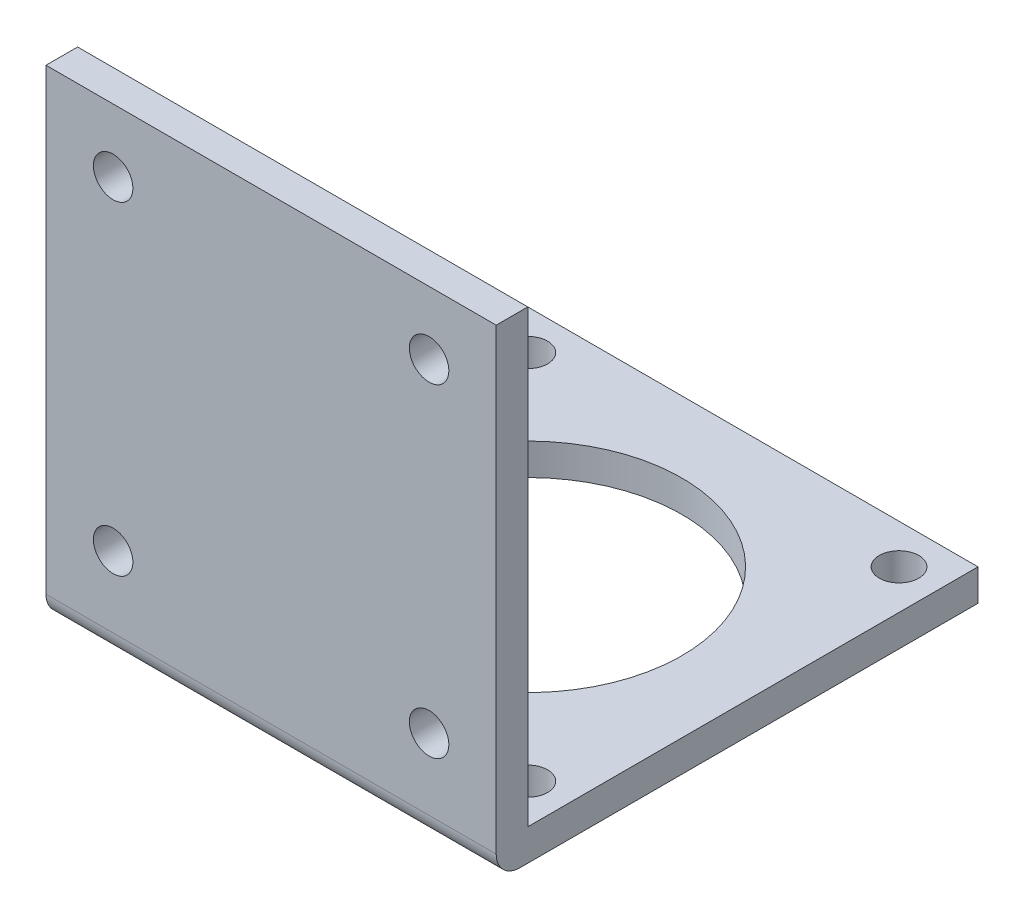
SolidWorks part; units mm, degrees
ref_plane "Front Plane" through (0, 0, 0) normal (0, 0, 1) x (1, 0, 0)
ref_plane "Top Plane" through (0, 0, 0) normal (0, 1, 0) x (1, 0, 0)
ref_plane "Right Plane" through (0, 0, 0) normal (1, 0, 0) x (0, 0, -1)
sketch "Sketch1" plane through (0, 0, 0) normal (1, 0, 0) x (0, 0, -1)
  line L0 (0, 0) -> (0, -61)
  line L1 (0, -61) -> (61, -61)
  line L2 (61, -61) -> (61, -57)
  line L3 (61, -57) -> (4, -57)
  line L4 (4, -57) -> (4, 0)
  line L5 (4, 0) -> (0, 0)
  dimension "D1" = 61
  dimension "D2" = 61
  dimension "D3" = 57
  dimension "D4" = 57
extrude "Boss-Extrude4" add sketch "Sketch1" along normal blind 57
fillet "Fillet4" radius 3 1 edges at (28.5, -61, 0)
sketch "Sketch10" plane through (0, -57, 0) normal (0, 1, 0) x (1, 0, 0)
  line L0 (28.5, 61) -> (28.5, 4) construction
  line L1 (57, 61) -> (0, 61) construction
  line L2 (57, 4) -> (0, 4) construction
  line L3 (0, 32.5) -> (57, 32.5) construction
  line L4 (0, 61) -> (0, 4) construction
  line L5 (57, 61) -> (57, 4) construction
  circle A0 centre (5, 56) radius 2.5
  circle A1 centre (5, 9) radius 2.5
  circle A2 centre (52, 9) radius 2.5
  circle A3 centre (52, 56) radius 2.5
  circle A4 centre (28.5, 32.5) radius 19.5
  dimension "D1" = 5
  dimension "D2" = 5
  dimension "D5" = 39
  dimension "D3" = 47
  dimension "D4" = 47
extrude "Cut-Extrude5" cut sketch "Sketch10" against normal up to surface (4 mm away) up to face at (28.5, -61, -32)
sketch "Sketch11" plane through (0, 0, -4) normal (0, 0, -1) x (-1, 0, 0)
  line L0 (-28.5, -57) -> (-28.5, 0) construction
  line L1 (-57, -57) -> (0, -57) construction
  line L2 (-57, 0) -> (0, 0) construction
  line L3 (-57, -28.5) -> (0, -28.5) construction
  line L4 (-57, -57) -> (-57, 0) construction
  line L5 (0, -57) -> (0, 0) construction
  circle A0 centre (-48.5, -8) radius 2.5
  circle A1 centre (-48.5, -49) radius 2.5
  circle A2 centre (-8.5, -49) radius 2.5
  circle A3 centre (-8.5, -8) radius 2.5
  dimension "D1" = 5
  dimension "D2" = 5
  dimension "D3" = 41
  dimension "D4" = 40
extrude "Cut-Extrude6" cut sketch "Sketch11" against normal up to surface (4 mm away) up to face at (28.5, -29, 0)
